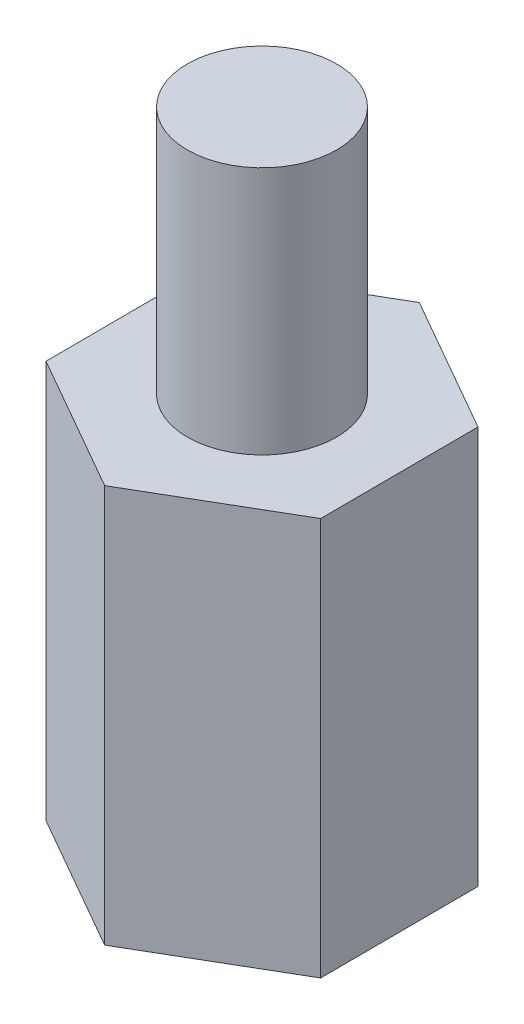
SolidWorks part; units mm, degrees
ref_plane "Alzado" through (0, 0, 0) normal (0, 0, 1) x (1, 0, 0)
ref_plane "Planta" through (0, 0, 0) normal (0, 1, 0) x (1, 0, 0)
ref_plane "Vista lateral" through (0, 0, 0) normal (1, 0, 0) x (0, 0, -1)
sketch "Croquis1" plane through (0, 0, 0) normal (0, 1, 0) x (1, 0, 0)
  line L1 (2.7435, 1.599) -> (-0.013, 3.1754)
  line L2 (-0.013, 3.1754) -> (-2.7565, 1.5764)
  line L3 (-2.7565, 1.5764) -> (-2.7435, -1.599)
  line L4 (-2.7435, -1.599) -> (0.013, -3.1754)
  line L5 (0.013, -3.1754) -> (2.7565, -1.5764)
  line L6 (2.7565, -1.5764) -> (2.7435, 1.599)
  circle A0 centre (0, 0) radius 2.75 construction
  dimension "D1" = 5.5
extrude "Saliente-Extruir1" add sketch "Croquis1" along normal blind 8
sketch "Croquis2" plane through (0, 8, 0) normal (0, 1, 0) x (1, 0, 0)
  circle A0 centre (0, 0) radius 1.5
  dimension "D1" = 3
extrude "Saliente-Extruir2" add sketch "Croquis2" along normal blind 5
cosmetic thread "Rosca cosmética1" parameters "D1"=5, "D2"=2.439
